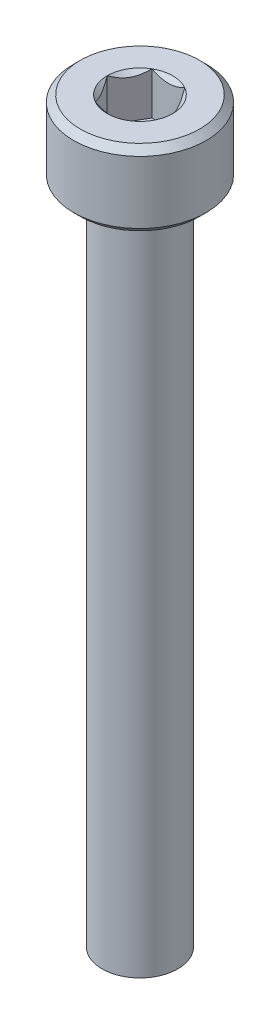
SolidWorks part; units mm, degrees
ref_plane "Front" through (0, 0, 0) normal (0, 0, 1) x (1, 0, 0)
ref_plane "Top" through (0, 0, 0) normal (0, 1, 0) x (1, 0, 0)
ref_plane "Right" through (0, 0, 0) normal (1, 0, 0) x (0, 0, -1)
sketch "Sketch1" plane through (0, 0, 0) normal (0, 1, 0) x (1, 0, 0)
  circle A0 centre (0, 0) radius 3.5
  dimension "D1" = 7
extrude "Boss-Extrude1" add sketch "Sketch1" along normal blind 4
sketch "Sketch2" plane through (0, 4, 0) normal (0, 1, 0) x (1, 0, 0)
  line L1 (0.866, 1.5) -> (-0.866, 1.5)
  line L2 (-0.866, 1.5) -> (-1.7321, 0)
  line L3 (-1.7321, 0) -> (-0.866, -1.5)
  line L4 (-0.866, -1.5) -> (0.866, -1.5)
  line L5 (0.866, -1.5) -> (1.7321, 0)
  line L6 (1.7321, 0) -> (0.866, 1.5)
  circle A0 centre (0, 0) radius 1.5 construction
  point P10 (0, 1.5)
  dimension "D1" = 3
extrude "Cut-Extrude1" cut sketch "Sketch2" against normal blind 2.25
sketch "Sketch3" plane through (0, 4, 0) normal (0, 1, 0) x (1, 0, 0)
  circle A0 centre (0, 0) radius 1.7321
extrude "Cut-Extrude2" cut sketch "Sketch3" against normal through all draft 45
chamfer "Chamfer1" distance 0.35 angle 45 2 edges at (0, 0, 3.5) (0, 4, 3.5)
sketch "草图1" plane through (0, 0, 0) normal (0, -1, 0) x (-1, 0, 0)
  circle A0 centre (0, 0) radius 2
  dimension "D1" = 4
extrude "凸台-拉伸1" add sketch "草图1" along normal blind 35
